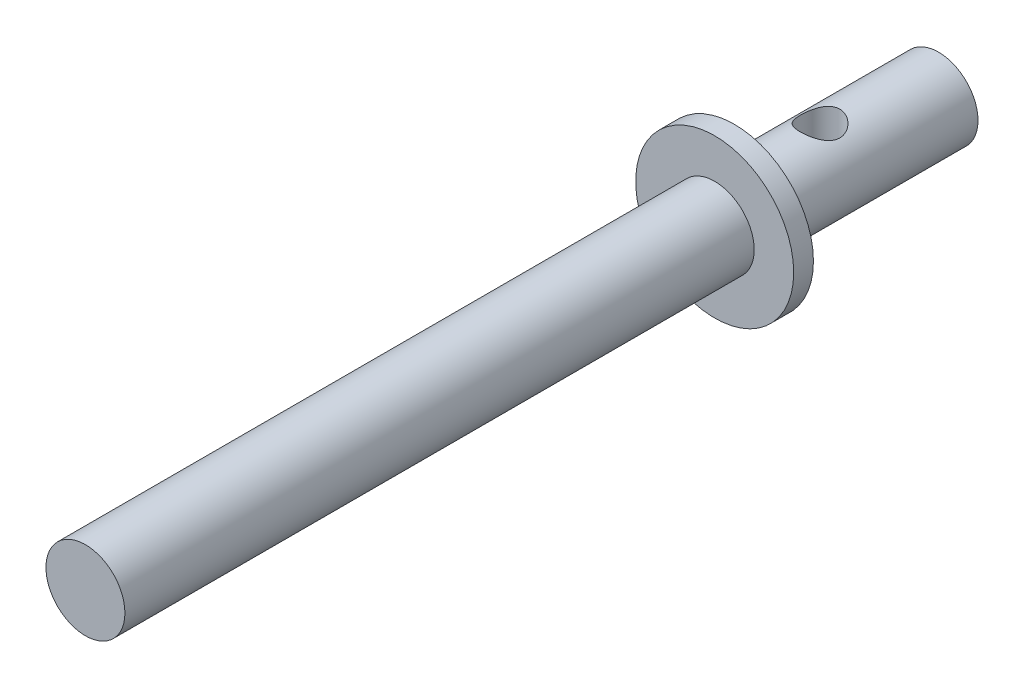
SolidWorks part; units mm, degrees
ref_plane "前视基准面" through (0, 0, 0) normal (0, 0, 1) x (1, 0, 0)
ref_plane "上视基准面" through (0, 0, 0) normal (0, 1, 0) x (1, 0, 0)
ref_plane "右视基准面" through (0, 0, 0) normal (1, 0, 0) x (0, 0, -1)
sketch "草图1" plane through (0, 0, 0) normal (0, 0, 1) x (1, 0, 0)
  circle A0 centre (0, 0) radius 3
extrude "凸台-拉伸1" add sketch "草图1" along normal blind 64.8
sketch3d "3D草图1"
  line L0 (0, 0, 0) -> (0, 0, 64.8) construction
  line L1 (0, 0, 64.8) -> (0, 0, 0) construction
  line L2 (0, 0, 0) -> (0, -3, 0) construction
  line L3 (0, 0, 17) -> (0, 11.1184, 17) construction
  circle A0 centre (0, 0, 0) radius 3 construction
  point P8 (0, 0, 3)
  dimension "D1" = 17
ref_plane "基准面1" through (0, 0, 17) normal (0, 0, 1) x (1, 0, 0)
sketch "草图2" plane through (0, 0, 17) normal (0, 0, 1) x (1, 0, 0)
  circle A0 centre (0, 0) radius 6
extrude "凸台-拉伸2" add sketch "草图2" along direction (0, 0, 1) on the side against the normal blind 1.5
ref_plane "基准面2" through (0, 0, 0) normal (1, 0, 0) x (0, 0, -1)
sketch "草图9" plane through (0, 0, 0) normal (1, 0, 0) x (0, 0, -1)
  line L0 (0, 0) -> (-64.8, 0) construction
  line L1 (-9, 0) -> (-9, -6.3299) construction
  point P0 (-9, 0)
  dimension "D1" = 9
ref_plane "基准面3" through (0, -6.3299, 9) normal (0, -1, 0) x (-1, 0, 0)
sketch "草图10" plane through (0, -6.3299, 9) normal (0, -1, 0) x (-1, 0, 0)
  circle A0 centre (0, 0) radius 1.5
extrude "切除-拉伸1" cut sketch "草图10" against normal blind 10
